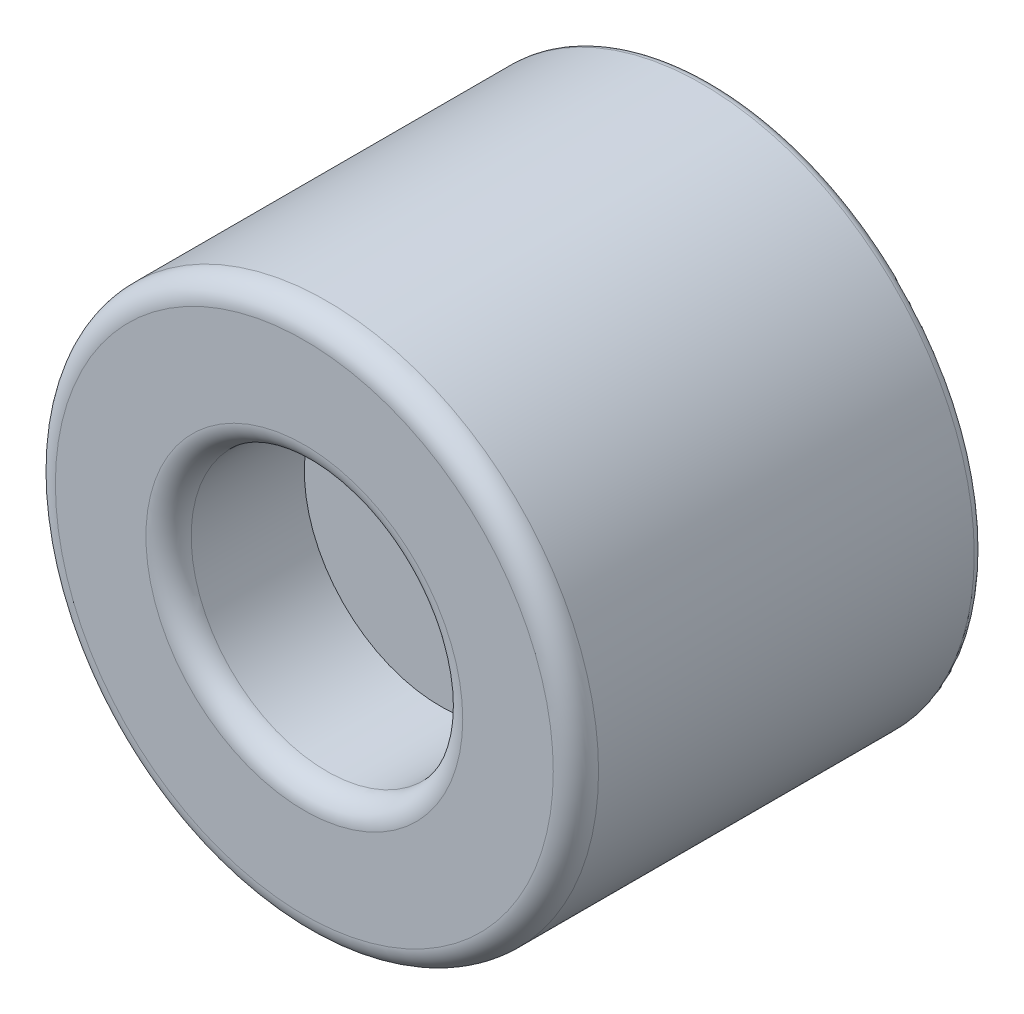
SolidWorks part; units mm, degrees
ref_plane "前视基准面" through (0, 0, 0) normal (0, 0, 1) x (1, 0, 0)
ref_plane "上视基准面" through (0, 0, 0) normal (0, 1, 0) x (1, 0, 0)
ref_plane "右视基准面" through (0, 0, 0) normal (1, 0, 0) x (0, 0, -1)
other "Configuration Table"
sketch "草图1" plane through (0, 0, 0) normal (0, 0, 1) x (1, 0, 0)
  circle A0 centre (0, 0) radius 6
  circle A1 centre (0, 0) radius 4.5
  dimension "D1" = 9
  dimension "D2" = 12
extrude "凸台-拉伸1" add sketch "草图1" along normal blind 3
sketch "草图2" plane through (0, 0, 3) normal (0, 0, 1) x (1, 0, 0)
  circle A0 centre (0, 0) radius 6
  dimension "D1" = 12
extrude "凸台-拉伸2" add sketch "草图2" along normal blind 6
sketch "草图3" plane through (0, 0, 9) normal (0, 0, 1) x (1, 0, 0)
  circle A0 centre (0, 0) radius 3
  dimension "D1" = 6
extrude "切除-拉伸1" cut sketch "草图3" against normal blind 3
fillet "圆角1" radius 0.5 1 edges at (3, 0, 9)
fillet "圆角2" radius 0.5 1 edges at (6, 0, 9)
fillet "圆角3" radius 0.2 2 edges at (4.5, 0, 0) (6, 0, 0)
